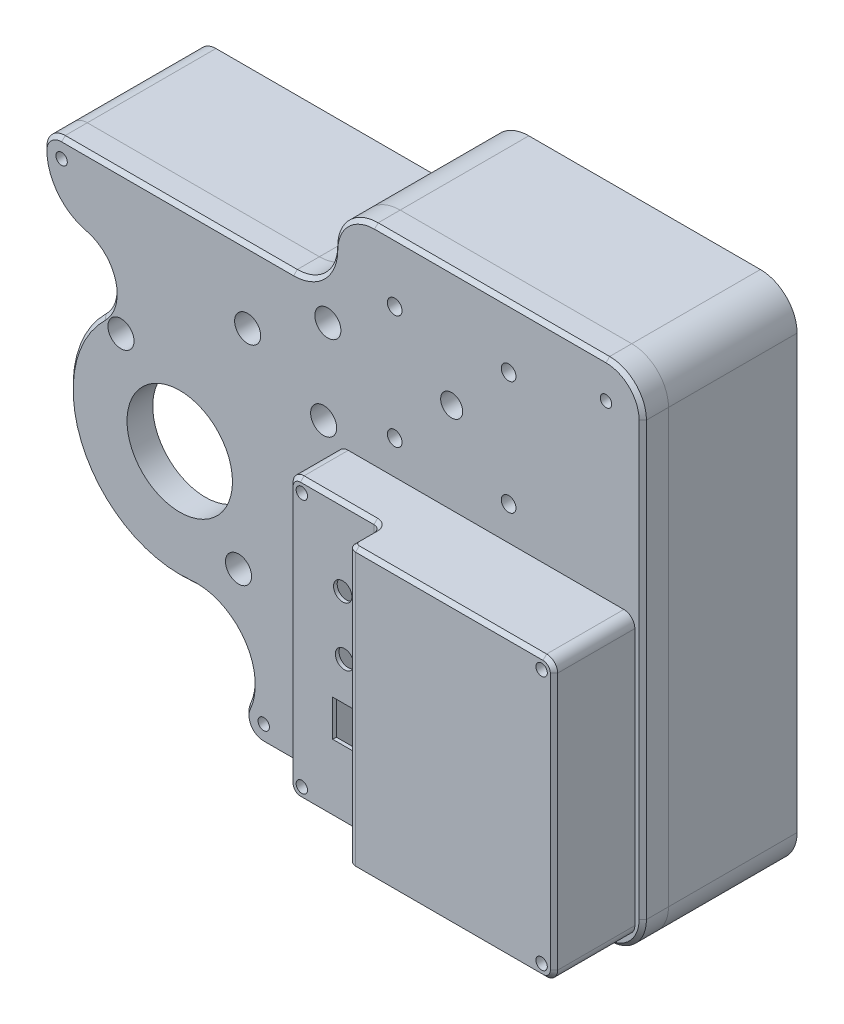
SolidWorks part; units mm, degrees
ref_plane "Front Plane" through (0, 0, 0) normal (1, 0, 0) x (0, 1, 0)
ref_plane "Top Plane" through (0, 0, 0) normal (0, 0, 1) x (0, 1, 0)
ref_plane "Right Plane" through (0, 0, 0) normal (0, 1, 0) x (-1, 0, 0)
sketch "Sketch1" plane through (0, 0, 0) normal (0, 0, 1) x (1, 0, 0)
  line L0 (47.85, 47.85) -> (-47.85, 47.85) construction
  line L1 (91, 25.85) -> (57, 25.85)
  line L2 (96, 30.85) -> (96, 64.85)
  line L3 (91, 69.85) -> (57, 69.85)
  line L4 (52, 30.85) -> (52, 64.85)
  line L5 (96, 25.85) -> (52, 69.85) construction
  line L6 (96, 69.85) -> (52, 25.85) construction
  line L7 (-32.15, 57.85) -> (31, 57.85)
  line L8 (-32.15, 47.85) -> (47.85, 47.85)
  line L9 (47.85, 47.85) -> (47.85, 18.15)
  line L10 (47.85, 18.15) -> (106, 18.15)
  line L12 (53, 79.85) -> (116, 79.85)
  line L13 (126, 69.85) -> (126, -47.85)
  line L14 (116, -57.85) -> (22.85, -57.85)
  line L15 (-47.85, -47.85) -> (47.85, -47.85) construction
  line L16 (22.85, -47.85) -> (106, -47.85)
  line L18 (116, -37.85) -> (116, 8.15)
  line L20 (42, 68.85) -> (42, 81.7098) construction
  arc A0 (57, 25.85) -> (52, 30.85) centre (57, 30.85) cw
  arc A1 (91, 25.85) -> (96, 30.85) centre (91, 30.85) ccw
  arc A2 (96, 64.85) -> (91, 69.85) centre (91, 64.85) ccw
  arc A3 (57, 69.85) -> (52, 64.85) centre (57, 64.85) ccw
  arc A4 (-32.15, 47.85) -> (-32.15, 57.85) centre (-32.15, 52.85) cw
  arc A5 (31, 57.85) -> (42, 68.85) centre (31, 68.85) ccw
  arc A6 (42, 68.85) -> (53, 79.85) centre (53, 68.85) cw
  arc A7 (22.85, -57.85) -> (22.85, -47.85) centre (22.85, -52.85) cw
  arc A8 (116, 79.85) -> (126, 69.85) centre (116, 69.85) cw
  arc A9 (106, 18.15) -> (116, 8.15) centre (106, 8.15) cw
  arc A10 (126, -47.85) -> (116, -57.85) centre (116, -47.85) cw
  arc A11 (106, -47.85) -> (116, -37.85) centre (106, -37.85) ccw
  point P0 (74, 47.85)
  point P52 (116, 18.15)
  point P57 (116, -47.85)
  dimension "D2" = 5
  dimension "D3" = 5
  dimension "D7" = 5
  dimension "D11" = 10
  dimension "D1" = 44
  dimension "D4" = 10
  dimension "D5" = 30
  dimension "D6" = 10
  dimension "D10" = 10
extrude "Boss-Extrude1" add sketch "Sketch1" along normal up to surface (35 mm away)
sketch "Sketch3" plane through (0, 0, 35) normal (0, 0, 1) x (1, 0, 0)
  line L0 (22.85, -57.85) -> (116, -57.85) construction
  line L1 (126, -47.85) -> (126, 69.85) construction
  line L2 (116, 79.85) -> (53, 79.85) construction
  line L3 (31, 57.85) -> (-32.15, 57.85) construction
  line L4 (22.85, -57.85) -> (116, -57.85)
  line L5 (126, -47.85) -> (126, 69.85)
  line L6 (116, 79.85) -> (53, 79.85)
  line L7 (31, 57.85) -> (-32.15, 57.85)
  arc A0 (22.85, -47.85) -> (22.85, -57.85) centre (22.85, -52.85) ccw construction
  arc A1 (-32.15, 57.85) -> (-32.15, 47.85) centre (-32.15, 52.85) ccw construction
  arc A2 (116, -57.85) -> (126, -47.85) centre (116, -47.85) ccw construction
  arc A3 (126, 69.85) -> (116, 79.85) centre (116, 69.85) ccw construction
  arc A4 (53, 79.85) -> (42, 68.85) centre (53, 68.85) ccw construction
  arc A5 (31, 57.85) -> (42, 68.85) centre (31, 68.85) ccw construction
  arc A6 (18.2763, -50.8297) -> (22.85, -57.85) centre (22.85, -52.85) ccw
  arc A7 (-32.15, 57.85) -> (-37.15, 52.85) centre (-32.15, 52.85) ccw
  arc A8 (116, -57.85) -> (126, -47.85) centre (116, -47.85) ccw
  arc A9 (126, 69.85) -> (116, 79.85) centre (116, 69.85) ccw
  arc A10 (53, 79.85) -> (42, 68.85) centre (53, 68.85) ccw
  arc A11 (31, 57.85) -> (42, 68.85) centre (31, 68.85) ccw
  arc A12 (-21.0133, 21.4113) -> (3.0369, -29.8459) centre (0, 0) ccw
  arc A13 (3.0369, -29.8459) -> (18.2763, -50.8297) centre (4.5553, -44.7688) cw
  arc A15 (-37.15, 52.85) -> (-25.6706, 38.269) centre (-22.15, 52.85) ccw
  arc A16 (-25.6706, 38.269) -> (-21.0133, 21.4113) centre (-28.0177, 28.5484) cw
  circle A17 centre (58.5, 63.35) radius 2
  circle A18 centre (89.5, 63.35) radius 2
  circle A19 centre (89.5, 32.35) radius 2
  circle A20 centre (58.5, 32.35) radius 2
  circle A21 centre (55.85, 10.65) radius 2.3
  circle A22 centre (110.85, 10.65) radius 2.3
  circle A23 centre (55.85, -41.35) radius 2.3
  circle A24 centre (110.85, -41.35) radius 2.3
  circle A25 centre (0, 0) radius 14.351
  circle A26 centre (74, 47.85) radius 3
  dimension "D1" = 30
  dimension "D2" = 10
  dimension "D3" = 15
  dimension "D4" = 15
  dimension "D5" = 4
  dimension "D6" = 4.6
  dimension "D7" = 28.702
  dimension "D8" = 6
extrude "Boss-Extrude2" add sketch "Sketch3" along normal blind 7 separate body
sketch "Sketch4" plane through (0, 0, 35) normal (0, 0, 1) x (1, 0, 0)
  circle A0 centre (-32.15, 52.85) radius 2.3
  circle A1 centre (22.85, -52.85) radius 2.3
  circle A2 centre (116, 69.85) radius 2.3
  dimension "D1" = 4.6
extrude "Cut-Extrude1" cut sketch "Sketch4" against normal blind 5
sketch "Sketch5" plane through (0, 0, 42) normal (0, 0, 1) x (1, 0, 0)
  circle A0 centre (-32.15, 52.85) radius 1.55
  circle A1 centre (116, 69.85) radius 1.55
  circle A2 centre (22.85, -52.85) radius 1.55
  dimension "D1" = 3.1
extrude "Cut-Extrude2" cut sketch "Sketch5" against normal up to next (7 mm away)
sketch "Sketch6" plane through (0, 0, 0) normal (0, 0, -1) x (-1, 0, 0)
  line L0 (-57, 25.85) -> (-91, 25.85) construction
  line L1 (-84, 25.85) -> (-64, 25.85)
  line L2 (-84, 25.85) -> (-84, 18.15)
  line L3 (-84, 18.15) -> (-64, 18.15)
  line L4 (-64, 25.85) -> (-64, 18.15)
  line L5 (-47.85, 18.15) -> (-106, 18.15) construction
  point P8 (-74, 25.85)
  dimension "D1" = 20
extrude "Cut-Extrude3" cut sketch "Sketch6" against normal blind 20
fillet "Fillet1" radius 7 2 edges at (64, 22, 20) (84, 22, 20)
sketch "Sketch7" plane through (0, 0, 42) normal (0, 0, 1) x (1, 0, 0)
  line L1 (87.1103, 1.0837) -> (94.621, 1.0837)
  line L2 (87.1103, 1.0837) -> (87.1103, -13.1584)
  line L3 (87.1103, -13.1584) -> (94.621, -13.1584)
  line L4 (94.621, 1.0837) -> (94.621, -13.1584)
extrude "Cut-Extrude4" cut sketch "Sketch7" against normal through all
fillet "Fillet2" radius 2 4 edges at (94.621, -13.1584, 38.5) (87.1103, 1.0837, 38.5) (87.1103, -13.1584, 38.5) (94.621, 1.0837, 38.5)
sketch "Sketch8" plane through (0, 0, 42) normal (0, 0, 1) x (1, 0, 0)
  circle A0 centre (-15.9943, 19.7318) radius 3.55
  circle A1 centre (15.9943, -19.7318) radius 3.55
  dimension "D1" = 7.1
extrude "Cut-Extrude5" cut sketch "Sketch8" against normal up to next (7 mm away)
sketch "Sketch9" plane through (0, 0, 42) normal (0, 0, 1) x (1, 0, 0)
  line L0 (50.85, 18.15) -> (115.85, 18.15)
  line L1 (49.85, 16.15) -> (116.85, 16.15) construction
  line L2 (49.85, 16.15) -> (49.85, -45.85) construction
  line L3 (49.85, -45.85) -> (116.85, -45.85) construction
  line L4 (116.85, 16.15) -> (116.85, -45.85) construction
  line L5 (118.85, 15.15) -> (118.85, -44.85)
  line L6 (50.85, -47.85) -> (115.85, -47.85)
  line L7 (47.85, 15.15) -> (47.85, -44.85)
  line L8 (45.85, 23.15) -> (120.85, 23.15)
  line L9 (123.85, 20.15) -> (123.85, -49.85)
  line L10 (45.85, -52.85) -> (120.85, -52.85)
  line L11 (42.85, 20.15) -> (42.85, -49.85)
  line L12 (47.85, -47.85) -> (118.85, -47.85) construction
  line L13 (47.85, 18.15) -> (47.85, -47.85) construction
  line L14 (42.85, -52.85) -> (123.85, -52.85) construction
  line L15 (42.85, 23.15) -> (42.85, -52.85) construction
  line L16 (118.85, 18.15) -> (118.85, -47.85) construction
  line L17 (123.85, 23.15) -> (123.85, -52.85) construction
  line L18 (47.85, 18.15) -> (118.85, 18.15) construction
  line L19 (42.85, 23.15) -> (123.85, 23.15) construction
  line L20 (43.7287, 22.2713) -> (48.7287, 17.2713) construction
  line L21 (117.9713, 17.2713) -> (122.9713, 22.2713) construction
  line L23 (117.9713, -46.9713) -> (122.9713, -51.9713) construction
  line L25 (43.7287, -51.9713) -> (48.7287, -46.9713) construction
  arc A0 (50.85, -47.85) -> (47.85, -44.85) centre (50.85, -44.85) cw
  arc A1 (45.85, -52.85) -> (42.85, -49.85) centre (45.85, -49.85) cw
  arc A2 (118.85, -44.85) -> (115.85, -47.85) centre (115.85, -44.85) cw
  arc A3 (123.85, -49.85) -> (120.85, -52.85) centre (120.85, -49.85) cw
  arc A4 (115.85, 18.15) -> (118.85, 15.15) centre (115.85, 15.15) cw
  arc A5 (120.85, 23.15) -> (123.85, 20.15) centre (120.85, 20.15) cw
  arc A6 (45.85, 23.15) -> (42.85, 20.15) centre (45.85, 20.15) ccw
  arc A7 (50.85, 18.15) -> (47.85, 15.15) centre (50.85, 15.15) ccw
  circle A9 centre (46.2287, 19.7713) radius 1.55
  circle A10 centre (120.4713, 19.7713) radius 1.55
  circle A11 centre (120.4713, -49.4713) radius 1.55
  circle A12 centre (46.2287, -49.4713) radius 1.55
  dimension "D3" = 3
  dimension "D4" = 3.1
  dimension "D1" = 2
  dimension "D2" = 5
extrude "Boss-Extrude3" add sketch "Sketch9" along normal blind 12 separate body
sketch "Sketch10" plane through (0, 0, 54) normal (0, 0, 1) x (1, 0, 0)
  line L0 (42.85, 20.15) -> (42.85, -49.85) construction
  line L1 (42.85, 20.15) -> (42.85, -49.85)
  line L2 (45.85, -52.85) -> (67.85, -52.85)
  line L3 (45.85, -52.85) -> (120.85, -52.85) construction
  line L4 (67.85, -52.85) -> (67.85, 23.15)
  line L5 (120.85, 23.15) -> (45.85, 23.15) construction
  line L6 (67.85, 23.15) -> (45.85, 23.15)
  line L8 (54.6243, -24.1129) -> (60.4829, -24.1129)
  line L9 (54.6243, -24.1129) -> (54.6243, -34.0633)
  line L10 (54.6243, -34.0633) -> (60.4829, -34.0633)
  line L11 (60.4829, -24.1129) -> (60.4829, -34.0633)
  arc A0 (45.85, 23.15) -> (42.85, 20.15) centre (45.85, 20.15) ccw construction
  arc A1 (42.85, -49.85) -> (45.85, -52.85) centre (45.85, -49.85) ccw construction
  arc A2 (42.85, -49.85) -> (45.85, -52.85) centre (45.85, -49.85) ccw
  arc A3 (45.85, 23.15) -> (42.85, 20.15) centre (45.85, 20.15) ccw
  circle A4 centre (46.2287, 19.7713) radius 1.55
  circle A5 centre (46.2287, -49.4713) radius 1.55
  circle A6 centre (57.35, 2.15) radius 2.5
  circle A7 centre (57.85, -13.58) radius 2.5
  dimension "D2" = 5
  dimension "D1" = 25
extrude "Boss-Extrude4" add sketch "Sketch10" along normal blind 1
sketch "Sketch11" plane through (0, 0, 54) normal (0, 0, 1) x (1, 0, 0)
  line L9 (67.85, -52.85) -> (67.85, 23.15)
  line L10 (115.85, 18.15) -> (68.85, 18.15)
  line L11 (115.85, 18.15) -> (67.85, 18.15) construction
  line L12 (68.85, 18.15) -> (68.85, -47.85)
  line L13 (67.85, -47.85) -> (115.85, -47.85) construction
  line L14 (68.85, -47.85) -> (115.85, -47.85)
  line L16 (67.85, -47.85) -> (67.85, -52.85)
  line L17 (67.85, -52.85) -> (120.85, -52.85)
  line L18 (123.85, -49.85) -> (123.85, 20.15)
  line L19 (120.85, 23.15) -> (67.85, 23.15)
  line L20 (67.85, 23.15) -> (67.85, 18.15)
  line L21 (67.85, 18.15) -> (115.85, 18.15)
  line L22 (118.85, 15.15) -> (118.85, -44.85)
  line L23 (115.85, -47.85) -> (67.85, -47.85)
  line L25 (67.85, -52.85) -> (120.85, -52.85)
  line L26 (123.85, -49.85) -> (123.85, 20.15)
  line L27 (120.85, 23.15) -> (67.85, 23.15)
  line L30 (118.85, 15.15) -> (118.85, -44.85)
  circle A4 centre (120.4713, 19.7713) radius 1.55
  circle A5 centre (120.4713, -49.4713) radius 1.55
  arc A8 (120.85, -52.85) -> (123.85, -49.85) centre (120.85, -49.85) ccw
  arc A9 (123.85, 20.15) -> (120.85, 23.15) centre (120.85, 20.15) ccw
  arc A10 (118.85, 15.15) -> (115.85, 18.15) centre (115.85, 15.15) ccw
  arc A11 (115.85, -47.85) -> (118.85, -44.85) centre (115.85, -44.85) ccw
  arc A12 (120.85, -52.85) -> (123.85, -49.85) centre (120.85, -49.85) ccw
  arc A13 (123.85, 20.15) -> (120.85, 23.15) centre (120.85, 20.15) ccw
  arc A14 (118.85, 15.15) -> (115.85, 18.15) centre (115.85, 15.15) ccw
  arc A15 (115.85, -47.85) -> (118.85, -44.85) centre (115.85, -44.85) ccw
  dimension "D2" = 1
  dimension "D1" = 0
extrude "Boss-Extrude5" add sketch "Sketch11" along normal blind 9
sketch "Sketch12" plane through (0, 0, 63) normal (0, 0, 1) x (1, 0, 0)
  line L0 (67.85, -52.85) -> (120.85, -52.85) construction
  line L1 (67.85, 23.15) -> (67.85, -52.85) construction
  line L2 (120.85, 23.15) -> (67.85, 23.15) construction
  line L3 (123.85, -49.85) -> (123.85, 20.15) construction
  line L4 (67.85, -52.85) -> (120.85, -52.85)
  line L5 (67.85, 23.15) -> (67.85, -52.85)
  line L6 (120.85, 23.15) -> (67.85, 23.15)
  line L7 (123.85, -49.85) -> (123.85, 20.15)
  arc A0 (123.85, 20.15) -> (120.85, 23.15) centre (120.85, 20.15) ccw construction
  arc A1 (120.85, -52.85) -> (123.85, -49.85) centre (120.85, -49.85) ccw construction
  arc A2 (123.85, 20.15) -> (120.85, 23.15) centre (120.85, 20.15) ccw
  arc A3 (120.85, -52.85) -> (123.85, -49.85) centre (120.85, -49.85) ccw
  circle A4 centre (120.4713, 19.7713) radius 1.55
  circle A5 centre (120.4713, -49.4713) radius 1.55
extrude "Boss-Extrude6" add sketch "Sketch12" along normal blind 1
fillet "Fillet3" radius 2 1 edges at (67.85, -14.85, 55)
fillet "Fillet4" radius 2 1 edges at (67.85, -14.85, 64)
sketch "Sketch13" plane through (0, 0, 42) normal (0, 0, 1) x (1, 0, 0)
  circle A0 centre (39.1576, 26.8424) radius 3.55
  circle A1 centre (40.3029, 50.3995) radius 3.55
  circle A2 centre (18.4845, 38.1946) radius 3.55
  dimension "D1" = 7.1
extrude "Cut-Extrude6" cut sketch "Sketch13" against normal blind 6.8
chamfer "Chamfer1" distance 1 angle 45 16 edges at (95.35, 23.15, 64) (68.4358, 23.15, 63.4142) (122.9713, 22.2713, 64) (67.85, 23.15, 59.5) (123.85, -14.85, 64) (67.2642, 23.15, 55.5858) (122.9713, -51.9713, 64) (55.85, 23.15, 55) (95.35, -52.85, 64) (43.7287, 22.2713, 55) (68.4358, -52.85, 63.4142) (42.85, -14.85, 55) (67.85, -52.85, 59.5) (43.7287, -51.9713, 55) (67.2642, -52.85, 55.5858) (55.85, -52.85, 55)
chamfer "Chamfer2" distance 1 angle 45 14 edges at (45.2218, 76.6282, 42) (38.7782, 61.0718, 42) (84.5, 79.85, 42) (-0.575, 57.85, 42) (123.0711, 76.9211, 42) (-35.6855, 56.3855, 42) (126, 11, 42) (-33.9358, 43.5712, 42) (123.0711, -54.9211, 42) (-18.3788, 31.2113, 42) (69.425, -57.85, 42) (-27.159, -12.7432, 42) (18.6606, -55.5793, 42) (16.6923, -35.9544, 42)
